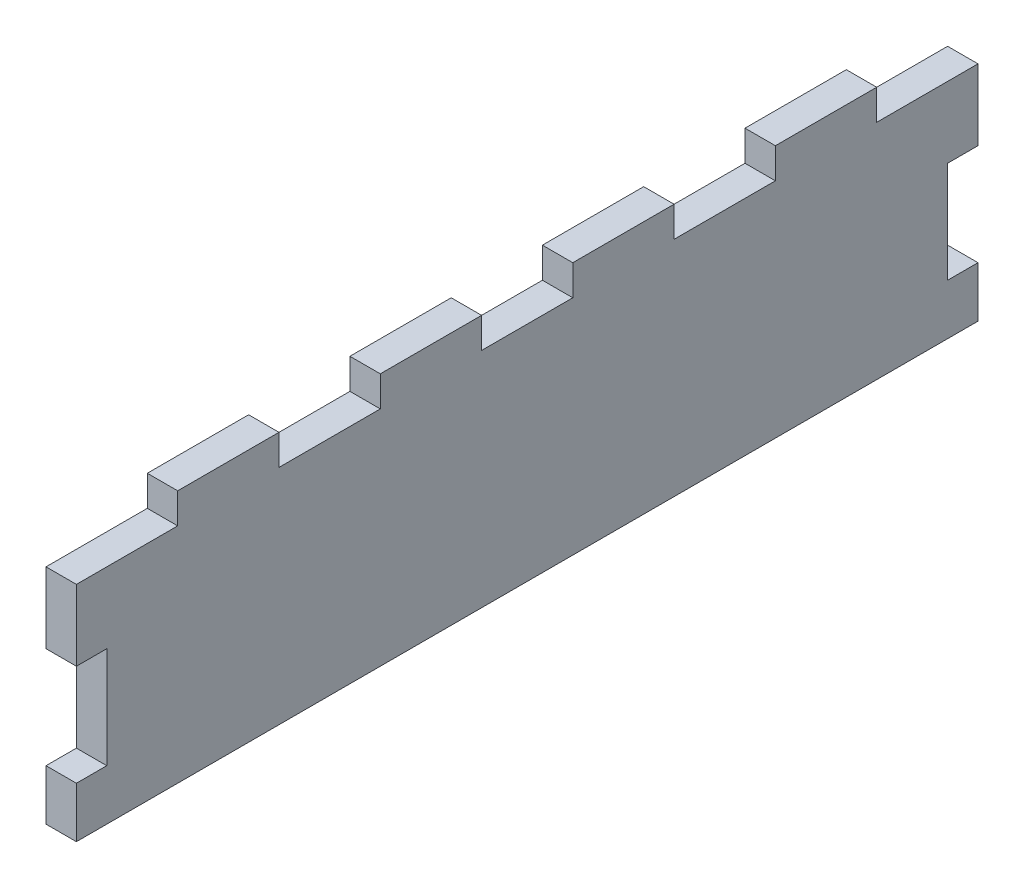
SolidWorks part; units mm, degrees
ref_plane "Front Plane" through (0, 0, 0) normal (0, 0, 1) x (1, 0, 0)
ref_plane "Top Plane" through (0, 0, 0) normal (0, 1, 0) x (1, 0, 0)
ref_plane "Right Plane" through (0, 0, 0) normal (1, 0, 0) x (0, 0, -1)
sketch "Sketch1" plane through (0, 0, 0) normal (1, 0, 0) x (0, 0, -1)
  line L0 (0, 15) -> (0, 22)
  line L1 (0, 0) -> (89, 0)
  line L2 (0, 0) -> (0, 5)
  line L3 (0, 22) -> (10, 22)
  line L4 (89, 0) -> (89, 5)
  line L5 (0, 15) -> (3, 15)
  line L6 (89, 15) -> (89, 22)
  line L7 (0, 5) -> (3, 5)
  line L8 (3, 15) -> (3, 5)
  line L9 (89, 15) -> (86, 15)
  line L10 (20, 22) -> (30, 22)
  line L11 (89, 5) -> (86, 5)
  line L12 (86, 15) -> (86, 5)
  line L14 (10, 22) -> (10, 25)
  line L15 (10, 25) -> (20, 25)
  line L16 (20, 22) -> (20, 25)
  line L18 (30, 22) -> (30, 25)
  line L19 (30, 25) -> (40, 25)
  line L20 (40, 22) -> (40, 25)
  line L22 (49, 22) -> (49, 25)
  line L23 (49, 25) -> (59, 25)
  line L24 (59, 22) -> (59, 25)
  line L26 (69, 22) -> (69, 25)
  line L27 (69, 25) -> (79, 25)
  line L28 (79, 22) -> (79, 25)
  line L29 (40, 22) -> (49, 22)
  line L30 (79, 22) -> (89, 22)
  line L31 (59, 22) -> (69, 22)
  dimension "D1" = 89
  dimension "D2" = 22
  dimension "D3" = 5
  dimension "D4" = 7
  dimension "D5" = 3
  dimension "D6" = 9
  dimension "D7" = 10
  dimension "D8" = 10
  dimension "D9" = 10
  dimension "D10" = 10
  dimension "D11" = 10
  dimension "D12" = 10
  dimension "D13" = 10
  dimension "D14" = 3
  dimension "D15" = 3
  dimension "D16" = 3
  dimension "D17" = 3
extrude "Boss-Extrude1" add sketch "Sketch1" along normal blind 3
